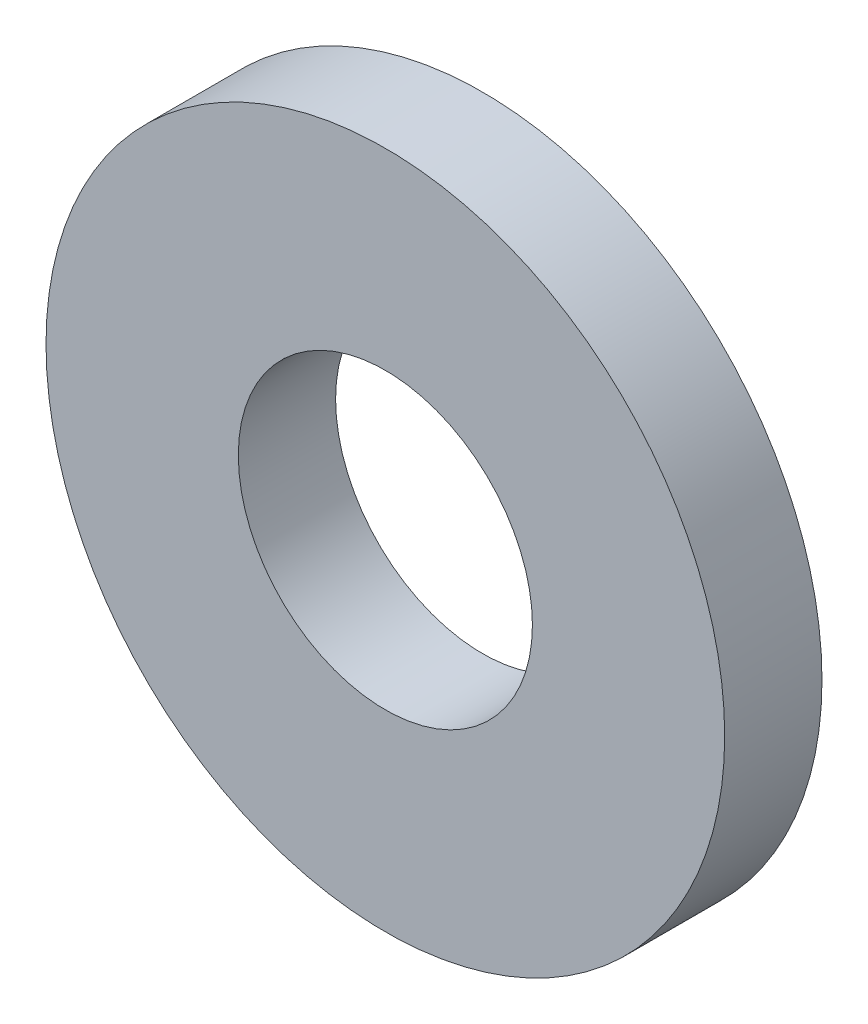
SolidWorks part; units mm, degrees
ref_plane "Front Plane" through (0, 0, 0) normal (0, 0, 1) x (1, 0, 0)
ref_plane "Top Plane" through (0, 0, 0) normal (0, 1, 0) x (1, 0, 0)
ref_plane "Right Plane" through (0, 0, 0) normal (1, 0, 0) x (0, 0, -1)
sketch "Sketch1" plane through (0, 0, 0) normal (0, 0, 1) x (1, 0, 0)
  circle A0 centre (0, 0) radius 3.81
  circle A1 centre (0, 0) radius 1.651
  dimension "D1" = 3.302
  dimension "D2" = 7.62
extrude "Boss-Extrude1" add sketch "Sketch1" along normal blind 1.0922
